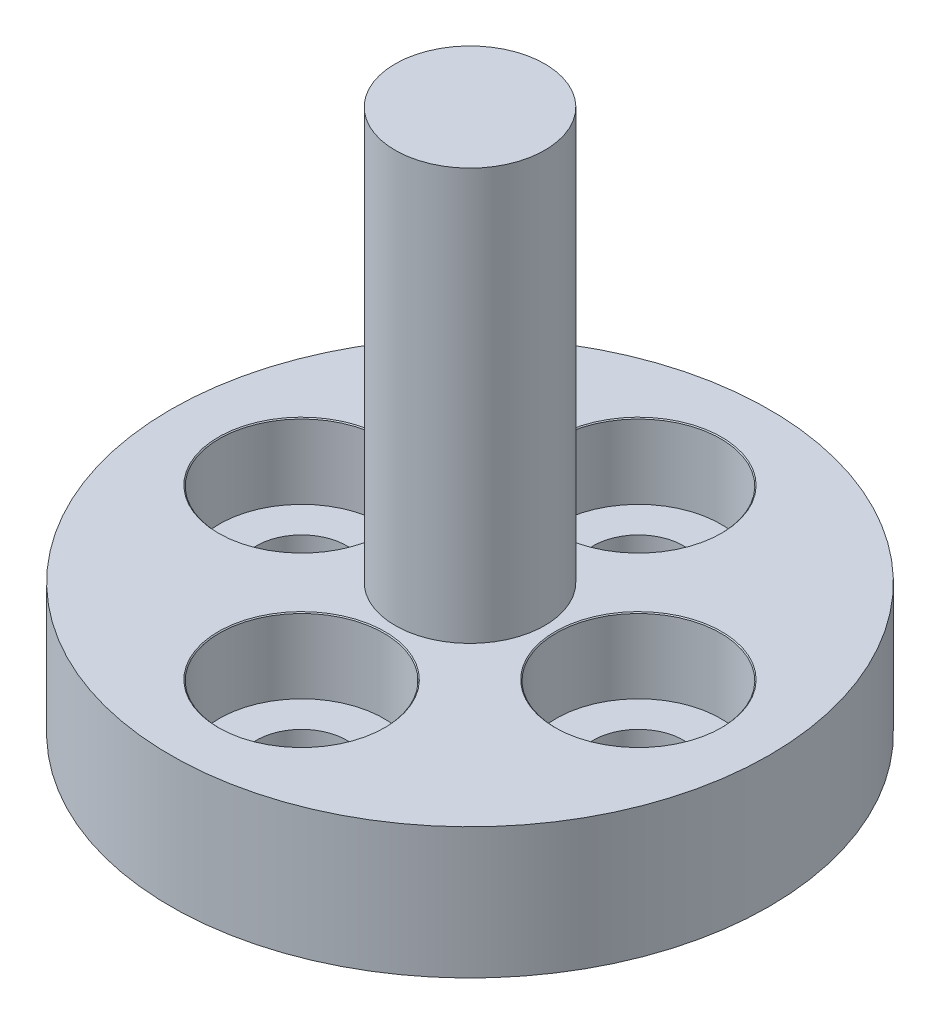
SolidWorks part; units mm, degrees
ref_plane "Front Plane" through (0, 0, 0) normal (0, 0, 1) x (1, 0, 0)
ref_plane "Top Plane" through (0, 0, 0) normal (0, 1, 0) x (1, 0, 0)
ref_plane "Right Plane" through (0, 0, 0) normal (1, 0, 0) x (0, 0, -1)
sketch "Sketch1" plane through (0, 0, 0) normal (0, 0, 1) x (1, 0, 0)
  line L0 (0, 0) -> (8, 0)
  line L1 (8, 0) -> (8, 3.5)
  line L2 (8, 3.5) -> (2, 3.5)
  line L3 (2, 3.5) -> (2, 14.5)
  line L4 (2, 14.5) -> (0, 14.5)
  line L5 (0, 14.5) -> (0, 0)
  dimension "D1" = 8
  dimension "D2" = 14.5
  dimension "D3" = 11
  dimension "D4" = 2
revolve "Revolve1" add sketch "Sketch1" angle 360 about L5
sketch "Sketch2" plane through (0, 3.5, 0) normal (0, 1, 0) x (1, 0, 0)
  circle A0 centre (0, 0) radius 4.5
  dimension "D1" = 9
hole_wizard "CBORE for M2 SHCS1" positions "Sketch3" profile "Sketch4" counterbore size "M2" standard "ANSI Metric" end condition through all
sketch "Sketch3" plane through (0, 3.5, 0) normal (0, 1, 0) x (1, 0, 0)
  circle A0 centre (0, 0) radius 4.5 construction
  point P0 (-4.5, 0)
  point P4 (0, 4.5)
  point P6 (4.5, 0)
  point P8 (0, -4.5)
sketch "Sketch4" plane through (-4.5, 3.5, 0) normal (1, 0, 0) x (0, 0, 1)
  line L0 (0, 0) -> (0, 3.5)
  line L1 (0, 3.5) -> (1.2, 3.5)
  line L3 (1.2, 3.5) -> (1.2, 2)
  line L4 (2.2, 2) -> (1.2, 2)
  line L5 (2.2, 2) -> (2.2, 0.025)
  line L6 (2.2, 0.025) -> (2.225, 0)
  line L7 (2.225, 0) -> (0, 0)
  line L8 (-2.2, 0.025) -> (-2.225, 0) construction
  line L11 (0, -6.35) -> (0, 107.95) construction
  dimension "Thru Hole Dia." = 2.4
  dimension "Thru Hole Depth" = 3.5
  dimension "C'Bore Dia." = 4.4
  dimension "C'Bore Depth" = 2
  dimension "Near C'Sink Dia." = 4.45
  dimension "Near C'Sink Angle" = 90
